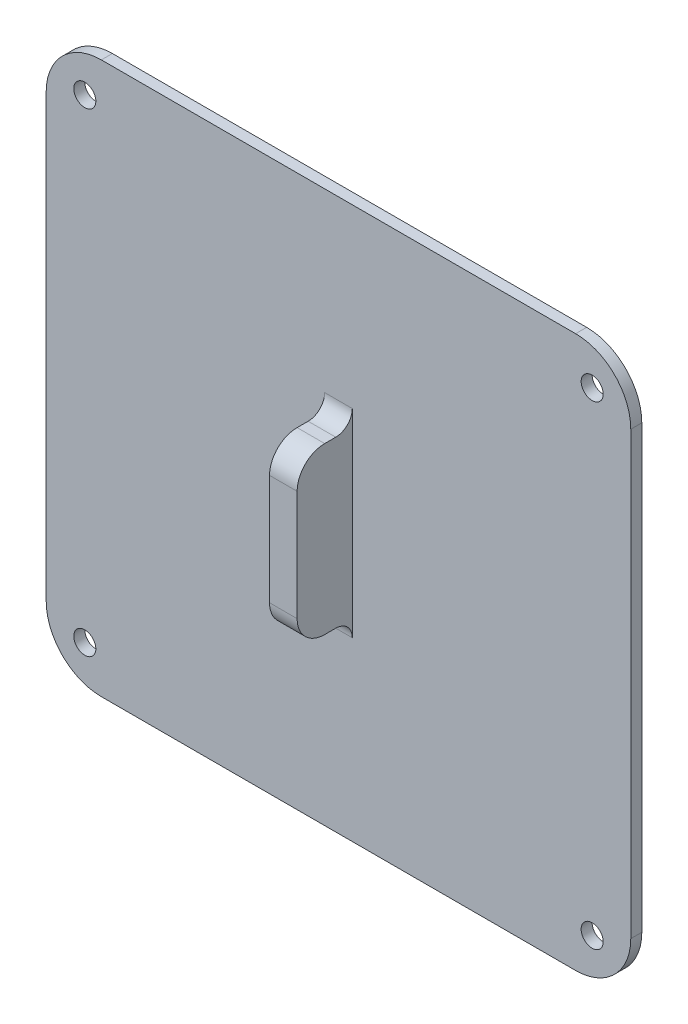
SolidWorks part; units mm, degrees
material "ABS"
ref_plane "Front Plane" through (0, 0, 0) normal (0, 0, 1) x (1, 0, 0)
ref_plane "Top Plane" through (0, 0, 0) normal (0, 1, 0) x (1, 0, 0)
ref_plane "Right Plane" through (0, 0, 0) normal (1, 0, 0) x (0, 0, -1)
sketch "Sketch1" plane through (0, 0, 0) normal (0, 0, 1) x (1, 0, 0)
  line L4 (-43, 260) -> (43, 260)
  line L5 (53, 270) -> (53, 350)
  line L6 (43, 360) -> (-43, 360)
  line L7 (-53, 350) -> (-53, 270)
  arc A4 (43, 260) -> (53, 270) centre (43, 270) ccw
  arc A5 (53, 350) -> (43, 360) centre (43, 350) ccw
  arc A6 (-43, 360) -> (-53, 350) centre (-43, 350) ccw
  arc A7 (-53, 270) -> (-43, 260) centre (-43, 270) ccw
extrude "Boss-Extrude1" add sketch "Sketch1" against normal blind 2
sketch "Sketch2" plane through (0, 0, -2) normal (0, 0, -1) x (-1, 0, 0)
  circle A4 centre (46, 267) radius 2
  circle A6 centre (-46, 267) radius 2
  circle A7 centre (-46, 353) radius 2
  circle A8 centre (46, 353) radius 2
extrude "Cut-Extrude1" cut sketch "Sketch2" against normal blind 3
sketch "Sketch6" plane through (0, 0, 0) normal (0, 0, 1) x (1, 0, 0)
  line L0 (0, 260) -> (0, 360) construction
  line L1 (-43, 260) -> (43, 260) construction
  line L2 (43, 360) -> (-43, 360) construction
  line L3 (-53, 310) -> (53, 310) construction
  line L4 (-2.5, 325) -> (2.5, 325)
  line L5 (-2.5, 325) -> (-2.5, 295)
  line L6 (-2.5, 295) -> (2.5, 295)
  line L7 (2.5, 325) -> (2.5, 295)
  line L8 (-53, 350) -> (-53, 270) construction
  line L9 (53, 270) -> (53, 350) construction
extrude "Boss-Extrude2" add sketch "Sketch6" along normal blind 10
fillet "Fillet1" radius 5 2 edges at (0, 325, 10) (0, 295, 10)
fillet "Fillet2" radius 3 2 edges at (0, 295, 0) (0, 325, 0)
